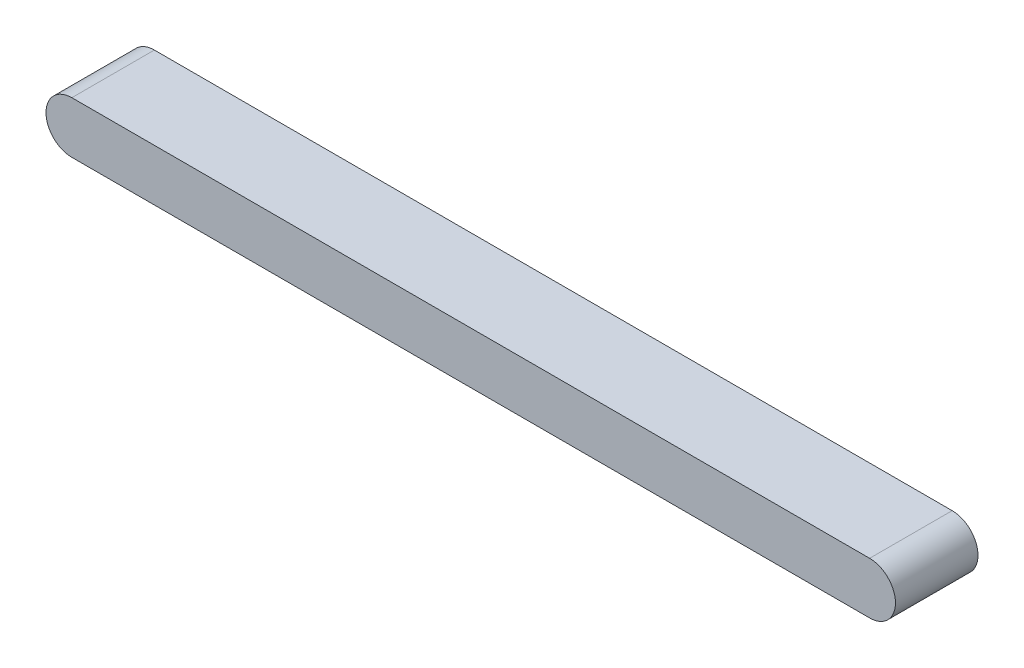
SolidWorks part; units mm, degrees
ref_plane "前视基准面" through (0, 0, 0) normal (0, 0, 1) x (1, 0, 0)
ref_plane "上视基准面" through (0, 0, 0) normal (0, 1, 0) x (1, 0, 0)
ref_plane "右视基准面" through (0, 0, 0) normal (1, 0, 0) x (0, 0, -1)
sketch "草图1" plane through (0, 0, 0) normal (0, 0, 1) x (1, 0, 0)
  line L0 (0, 0) -> (145, 0) construction
  line L1 (0, 4.6955) -> (145, 4.6955)
  line L2 (0, -4.6955) -> (145, -4.6955)
  arc A0 (0, 4.6955) -> (0, -4.6955) centre (0, 0) ccw
  arc A1 (145, -4.6955) -> (145, 4.6955) centre (145, 0) ccw
  point P0 (72.5, 0)
  point P8 (0.1801, 0)
  point P9 (0, 0)
  point P11 (145, 0)
  dimension "D1" = 145
extrude "凸台-拉伸1" add sketch "草图1" along normal mid plane 15
